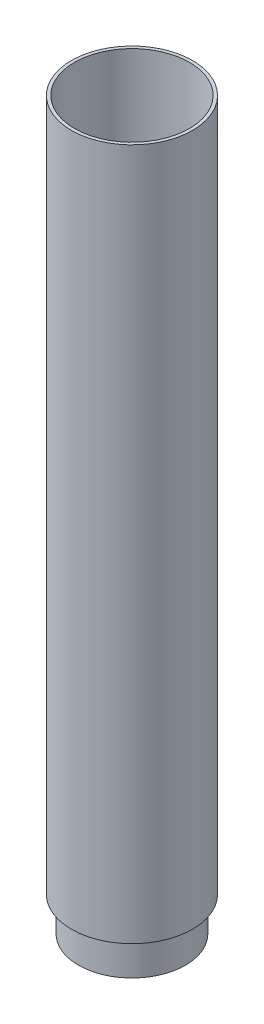
SolidWorks part; units mm, degrees
ref_plane "Front Plane" through (0, 0, 0) normal (0, 0, 1) x (1, 0, 0)
ref_plane "Top Plane" through (0, 0, 0) normal (0, 1, 0) x (1, 0, 0)
ref_plane "Right Plane" through (0, 0, 0) normal (1, 0, 0) x (0, 0, -1)
sketch "Sketch1" plane through (0, 0, 0) normal (0, 1, 0) x (1, 0, 0)
  circle A0 centre (0, 0) radius 15.5
  circle A1 centre (0, 0) radius 14
  dimension "D1" = 31
  dimension "D2" = 28
extrude "Boss-Extrude1" add sketch "Sketch1" along normal blind 10
sketch "Sketch4" plane through (0, 10, 0) normal (0, 1, 0) x (1, 0, 0)
  circle A0 centre (0, 0) radius 14
  circle A3 centre (0, 0) radius 17.5
  dimension "D1" = 28
  dimension "D2" = 35
extrude "Boss-Extrude2" add sketch "Sketch4" along normal blind 200
sketch "Sketch5" plane through (0, 210, 0) normal (0, 1, 0) x (1, 0, 0)
  circle A0 centre (0, 0) radius 16.6
  dimension "D2" = 33.2
extrude "Cut-Extrude2" cut sketch "Sketch5" against normal blind 195
